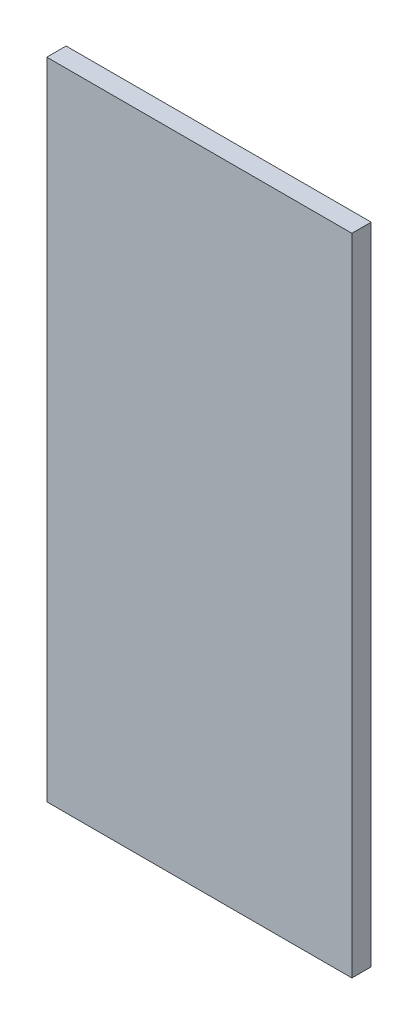
SolidWorks part; units mm, degrees
ref_plane "Front Plane" through (0, 0, 0) normal (0, 0, 1) x (1, 0, 0)
ref_plane "Top Plane" through (0, 0, 0) normal (0, 1, 0) x (1, 0, 0)
ref_plane "Right Plane" through (0, 0, 0) normal (1, 0, 0) x (0, 0, -1)
sketch "Sketch1" plane through (0, 0, 0) normal (0, 0, 1) x (1, 0, 0)
  line L0 (0, 1220) -> (0, -250) construction
  line L1 (-100, 1220) -> (100, 1220) construction
  line L2 (200, -250) -> (-200, -250) construction
  line L3 (-295, 780) -> (-295, 860) construction
  line L4 (395, -350) -> (-395, -350)
  line L5 (395, -350) -> (395, 1320)
  line L6 (395, 1320) -> (-395, 1320)
  line L7 (-395, -350) -> (-395, 1320)
  line L8 (395, -350) -> (-395, 1320) construction
  line L9 (395, 1320) -> (-395, -350) construction
  point P6 (0, 485)
  dimension "D1" = 100
  dimension "D2" = 100
extrude "Boss-Extrude1" add sketch "Sketch1" along normal blind 50
